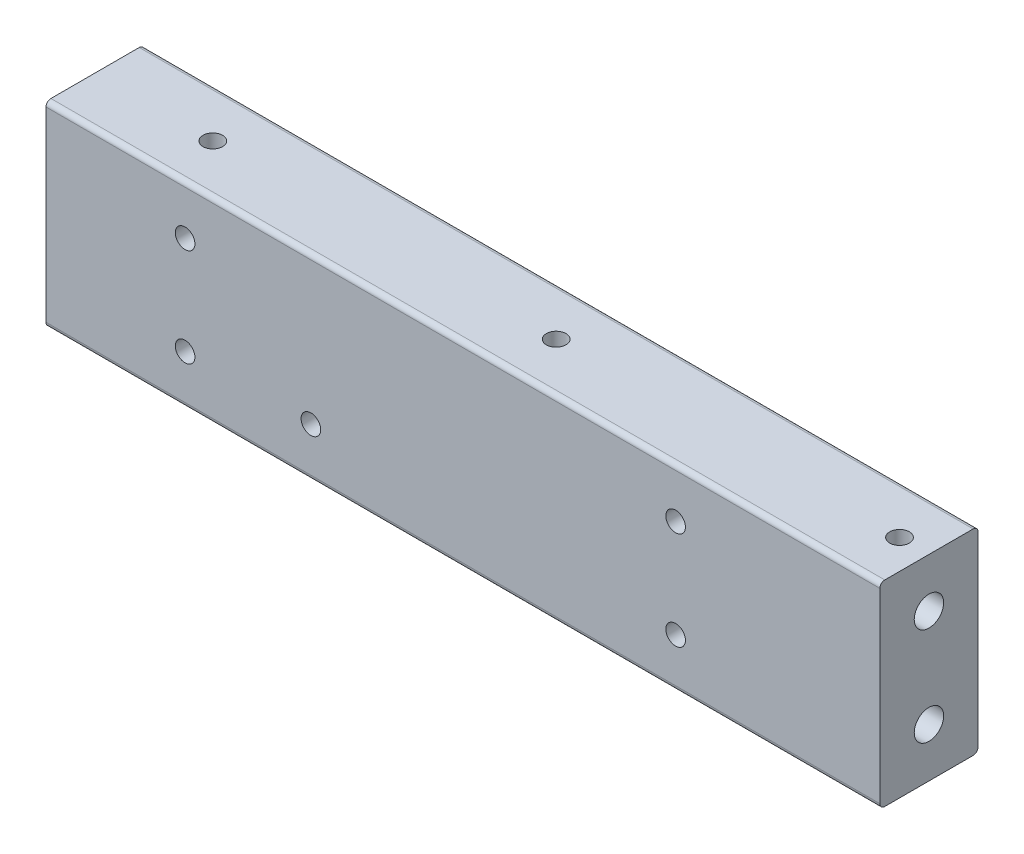
SolidWorks part; units mm, degrees
ref_plane "前视基准面" through (0, 0, 0) normal (0, 0, 1) x (1, 0, 0)
ref_plane "上视基准面" through (0, 0, 0) normal (0, 1, 0) x (1, 0, 0)
ref_plane "右视基准面" through (0, 0, 0) normal (1, 0, 0) x (0, 0, -1)
sketch "草图1" plane through (0, 0, 0) normal (0, 0, 1) x (1, 0, 0)
  line L1 (0, 0) -> (170, 0)
  line L2 (0, 0) -> (0, 40)
  line L3 (0, 40) -> (170, 40)
  line L4 (170, 0) -> (170, 40)
  dimension "D1" = 170
  dimension "D2" = 40
extrude "凸台-拉伸1" add sketch "草图1" along normal blind 20
fillet "圆角1" radius 1 4 edges at (85, 0, 0) (85, 0, 20) (85, 40, 0) (85, 40, 20)
sketch "草图2" plane through (0, 0, 0) normal (-1, 0, 0) x (0, 0, 1)
  line L0 (19, 40) -> (1, 40) construction
  line L1 (19, 0) -> (1, 0) construction
  circle A0 centre (10, 30) radius 3
  circle A1 centre (10, 10) radius 3
  point P8 (10, 40)
  dimension "D1" = 6
  dimension "D2" = 10
  dimension "D3" = 10
extrude "切除-拉伸1" cut sketch "草图2" against normal through all
sketch "草图4" plane through (0, 0, 0) normal (0, 0, -1) x (-1, 0, 0)
  circle A0 centre (-128.3553, 10) radius 2
  circle A1 centre (-128.3553, 30) radius 2
  circle A2 centre (-28.3553, 10) radius 2
  circle A3 centre (-28.3553, 30) radius 2
  dimension "D1" = 4
extrude "切除-拉伸2" cut sketch "草图4" against normal blind 20
sketch "草图6" plane through (0, 0, 0) normal (0, 0, -1) x (-1, 0, 0)
  line L0 (0, 39) -> (0, 1) construction
  line L1 (-170, 40) -> (0, 40) construction
  circle A0 centre (-54, 10) radius 2
  dimension "D1" = 4
  dimension "D2" = 54
  dimension "D3" = 30
extrude "切除-拉伸3" cut sketch "草图6" against normal blind 20
sketch "草图7" plane through (0, 0, 0) normal (0, -1, 0) x (1, 0, 0)
  circle A0 centre (164, 10) radius 2
  circle A1 centre (94, 10) radius 2
  circle A2 centre (24, 10) radius 2
  dimension "D1" = 4
extrude "切除-拉伸4" cut sketch "草图7" against normal blind 40
